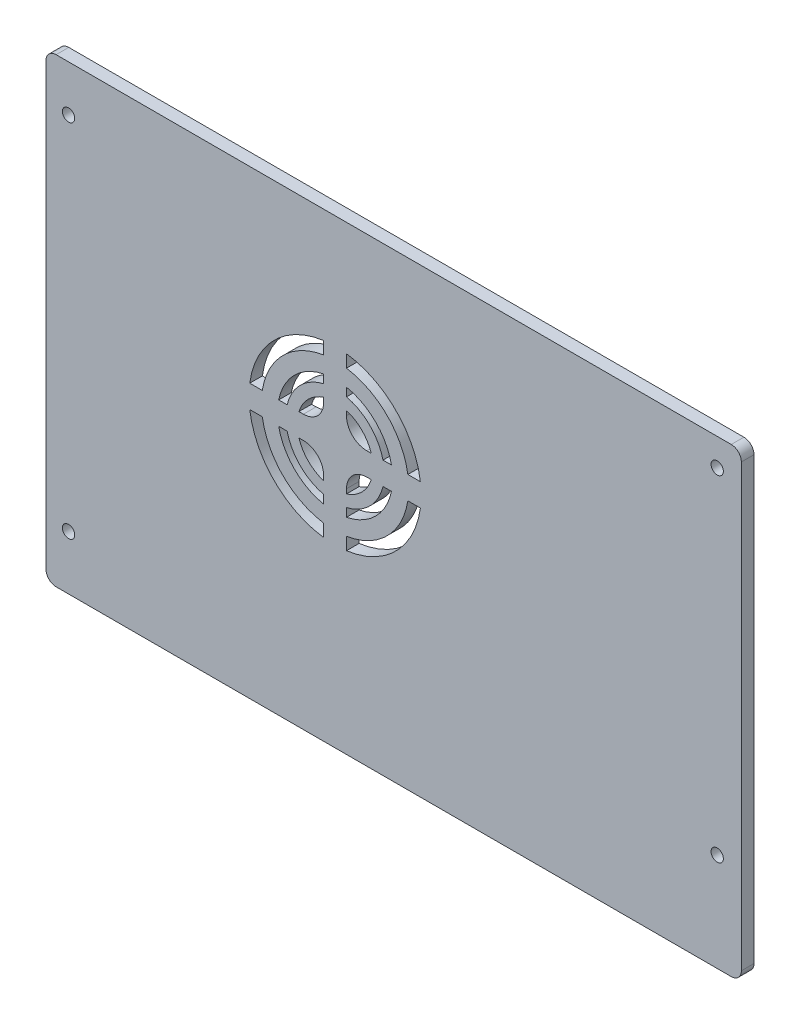
SolidWorks part; units mm, degrees
ref_plane "Front Plane" through (0, 0, 0) normal (0, 0, 1) x (1, 0, 0)
ref_plane "Top Plane" through (0, 0, 0) normal (0, 1, 0) x (1, 0, 0)
ref_plane "Right Plane" through (0, 0, 0) normal (1, 0, 0) x (0, 0, -1)
sketch "Sketch1" plane through (0, 0, 0) normal (0, 0, 1) x (1, 0, 0)
  line L0 (75.5113, 90.5563) -> (75.5113, 91.186)
  line L1 (0, 115.824) -> (174.752, 115.824)
  line L2 (0, 115.824) -> (0, 0)
  line L3 (0, 0) -> (174.752, 0)
  line L4 (174.752, 115.824) -> (174.752, 0)
  line L6 (49.784, 91.186) -> (95.504, 91.186)
  line L7 (87.376, 115.824) -> (87.376, 106.7862) construction
  line L8 (47.244, 88.646) -> (47.244, 42.926)
  line L9 (49.784, 40.386) -> (95.504, 40.386)
  line L10 (98.044, 88.646) -> (98.044, 42.926)
  line L11 (84.69, 62.9187) -> (86.8089, 62.9187)
  line L12 (60.598, 62.9187) -> (58.4791, 62.9187)
  line L13 (84.69, 68.6533) -> (86.8089, 68.6533)
  line L14 (75.5113, 53.74) -> (75.5113, 51.6211)
  line L16 (69.7767, 40.386) -> (75.5113, 40.386)
  line L17 (69.7767, 53.74) -> (69.7767, 51.6211)
  line L18 (69.7767, 77.832) -> (69.7767, 79.9509)
  line L19 (69.7767, 91.186) -> (75.5113, 91.186)
  line L20 (75.5113, 77.832) -> (75.5113, 79.9509)
  line L25 (69.7767, 90.5563) -> (69.7767, 91.186)
  line L26 (47.8737, 68.6533) -> (47.244, 68.6533)
  line L27 (47.8737, 62.9187) -> (47.244, 62.9187)
  line L28 (60.598, 68.6533) -> (58.4791, 68.6533)
  line L29 (54.3511, 68.6533) -> (51.2011, 68.6533)
  line L30 (54.3511, 62.9187) -> (51.2011, 62.9187)
  line L31 (75.5113, 84.0789) -> (75.5113, 87.2289)
  line L32 (69.7767, 84.0789) -> (69.7767, 87.2289)
  line L33 (90.9369, 68.6533) -> (94.0869, 68.6533)
  line L34 (90.9369, 62.9187) -> (94.0869, 62.9187)
  line L35 (75.5113, 47.4931) -> (75.5113, 44.3431)
  line L36 (69.7767, 47.4931) -> (69.7767, 44.3431)
  line L37 (97.4143, 68.6533) -> (98.044, 68.6533)
  line L38 (97.4143, 62.9187) -> (98.044, 62.9187)
  line L39 (75.5113, 41.0157) -> (75.5113, 40.386)
  line L40 (69.7767, 41.0157) -> (69.7767, 40.386)
  line L41 (69.7767, 74.8692) -> (69.7767, 73.7333)
  line L42 (75.5113, 74.8692) -> (75.5113, 73.7333)
  line L43 (63.5608, 68.6533) -> (64.6967, 68.6533)
  line L44 (81.7272, 62.9187) -> (80.5913, 62.9187)
  line L45 (69.7767, 57.8387) -> (69.7767, 56.7028)
  line L46 (75.5113, 57.8387) -> (75.5113, 56.7028)
  line L47 (80.5913, 68.6533) -> (81.7272, 68.6533)
  line L48 (64.6967, 62.9187) -> (63.5608, 62.9187)
  circle A0 centre (5.6642, 104.267) radius 1.5494
  circle A1 centre (168.6814, 108.966) radius 1.5494
  circle A2 centre (168.6814, 24.6888) radius 1.5494
  circle A3 centre (5.6642, 13.6144) radius 1.5494
  arc A4 (49.784, 40.386) -> (47.244, 42.926) centre (49.784, 42.926) cw
  arc A5 (95.504, 40.386) -> (98.044, 42.926) centre (95.504, 42.926) ccw
  arc A6 (98.044, 88.646) -> (95.504, 91.186) centre (95.504, 88.646) ccw
  arc A7 (47.244, 88.646) -> (49.784, 91.186) centre (49.784, 88.646) cw
  arc A8 (69.7767, 77.832) -> (60.598, 68.6533) centre (72.644, 65.786) ccw
  arc A9 (60.598, 62.9187) -> (69.7767, 53.74) centre (72.644, 65.786) ccw
  arc A10 (84.69, 68.6533) -> (75.5113, 77.832) centre (72.644, 65.786) ccw
  arc A11 (75.5113, 53.74) -> (84.69, 62.9187) centre (72.644, 65.786) ccw
  arc A27 (54.3511, 62.9187) -> (69.7767, 47.4931) centre (72.644, 65.786) ccw
  arc A28 (58.4791, 62.9187) -> (69.7767, 51.6211) centre (72.644, 65.786) ccw
  arc A29 (51.2011, 62.9187) -> (69.7767, 44.3431) centre (72.644, 65.786) ccw
  arc A30 (47.8737, 62.9187) -> (69.7767, 41.0157) centre (72.644, 65.786) ccw
  arc A31 (86.8089, 68.6533) -> (75.5113, 79.9509) centre (72.644, 65.786) ccw
  arc A33 (90.9369, 68.6533) -> (75.5113, 84.0789) centre (72.644, 65.786) ccw
  arc A34 (94.0869, 68.6533) -> (75.5113, 87.2289) centre (72.644, 65.786) ccw
  arc A35 (97.4143, 68.6533) -> (75.5113, 90.5563) centre (72.644, 65.786) ccw
  arc A36 (69.7767, 79.9509) -> (58.4791, 68.6533) centre (72.644, 65.786) ccw
  arc A37 (69.7767, 74.8692) -> (69.7767, 56.7028) centre (72.644, 65.786) ccw
  arc A38 (69.7767, 84.0789) -> (54.3511, 68.6533) centre (72.644, 65.786) ccw
  arc A39 (69.7767, 87.2289) -> (51.2011, 68.6533) centre (72.644, 65.786) ccw
  arc A40 (69.7767, 90.5563) -> (47.8737, 68.6533) centre (72.644, 65.786) ccw
  arc A41 (75.5113, 51.6211) -> (86.8089, 62.9187) centre (72.644, 65.786) ccw
  arc A42 (69.7767, 57.8387) -> (64.6967, 62.9187) centre (64.6967, 57.8387) ccw
  arc A43 (75.5113, 47.4931) -> (90.9369, 62.9187) centre (72.644, 65.786) ccw
  arc A44 (75.5113, 44.3431) -> (94.0869, 62.9187) centre (72.644, 65.786) ccw
  arc A45 (75.5113, 41.0157) -> (97.4143, 62.9187) centre (72.644, 65.786) ccw
  arc A46 (80.5913, 62.9187) -> (75.5113, 57.8387) centre (80.5913, 57.8387) ccw
  arc A47 (80.5913, 68.6533) -> (75.5113, 73.7333) centre (80.5913, 73.7333) cw
  arc A48 (64.6967, 68.6533) -> (69.7767, 73.7333) centre (64.6967, 73.7333) ccw
  arc A49 (81.7272, 68.6533) -> (75.5113, 74.8692) centre (72.644, 65.786) ccw
  arc A50 (75.5113, 56.7028) -> (81.7272, 62.9187) centre (72.644, 65.786) ccw
  circle A54 centre (5.6642, 104.267) radius 1.5494 construction
  circle A55 centre (168.6814, 108.966) radius 1.5494 construction
  circle A56 centre (168.6814, 24.6888) radius 1.5494 construction
  circle A57 centre (5.6642, 13.6144) radius 1.5494 construction
  point P21 (47.244, 65.786)
  point P24 (47.244, 40.386)
  point P29 (98.044, 91.186)
  point P32 (47.244, 91.186)
  point P42 (72.644, 84.2327)
  point P49 (72.644, 47.3393)
  dimension "D20" = 2.54
  dimension "D21" = 4.064
  dimension "D22" = 3.302
  dimension "D1" = 115.824
  dimension "D2" = 174.752
  dimension "D16" = 50.8
  dimension "D17" = 50.8
  dimension "D18" = 47.244
extrude "Boss-Extrude2" add sketch "Sketch1" along normal blind 3.175 contours L39 A45 L38 L10 L37 A35 L0 L6 L25 A40 L26 L8 L27 A30 L40 L9 A44 L35 A43 L34 A41 L14 A11 L11 A39 L32 A38 L29 A36 L18 A8 L28 A34 L33 A33 L31 A31 L13 A10 L20 A29 L30 A27 L36 | A40 L25 L6 A7 L8 L26 | A35 L37 L10 A6 L6 L0 | A45 L39 L9 A5 L10 L38 | A30 L27 L8 A4 L9 L40 | L4 L1 L2 L3 A0 A1 A2 A3 L8 A7 L6 A6 L10 A5 L9 A4
fillet "Fillet2" radius 2.54 4 edges at (174.752, 115.824, 1.5875) (174.752, 0, 1.5875) (0, 0, 1.5875) (0, 115.824, 1.5875)
